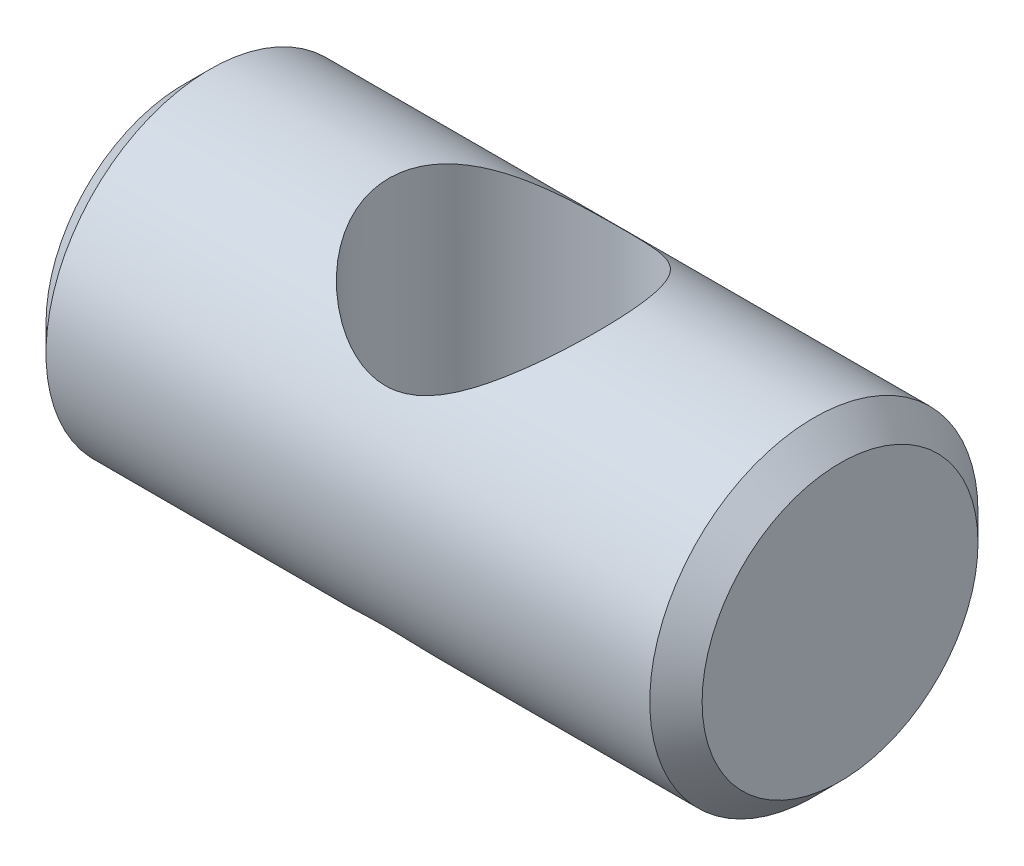
SolidWorks part; units mm, degrees
ref_plane "Front Plane" through (0, 0, 0) normal (0, 0, 1) x (1, 0, 0)
ref_plane "Top Plane" through (0, 0, 0) normal (0, 1, 0) x (1, 0, 0)
ref_plane "Right Plane" through (0, 0, 0) normal (1, 0, 0) x (0, 0, -1)
sketch "Sketch1" plane through (0, 0, 0) normal (1, 0, 0) x (0, 0, -1)
  circle A0 centre (0, 0) radius 4.765
  dimension "D1" = 9.53
extrude "Boss-Extrude1" add sketch "Sketch1" along normal mid plane 19.05
chamfer "Chamfer1" distance 0.76 angle 45 2 edges at (-9.525, 0, -4.765) (9.525, 0, -4.765)
sketch "Sketch2" plane through (0, 0, 0) normal (0, 1, 0) x (1, 0, 0)
  circle A0 centre (0, -0.25) radius 3.43
  point P2 (0, 0)
  point P5 (-0.108, -0.0713)
  dimension "D1" = 6.86
  dimension "D2" = 0.25
extrude "Cut-Extrude1" cut sketch "Sketch2" against normal mid plane 19.05
